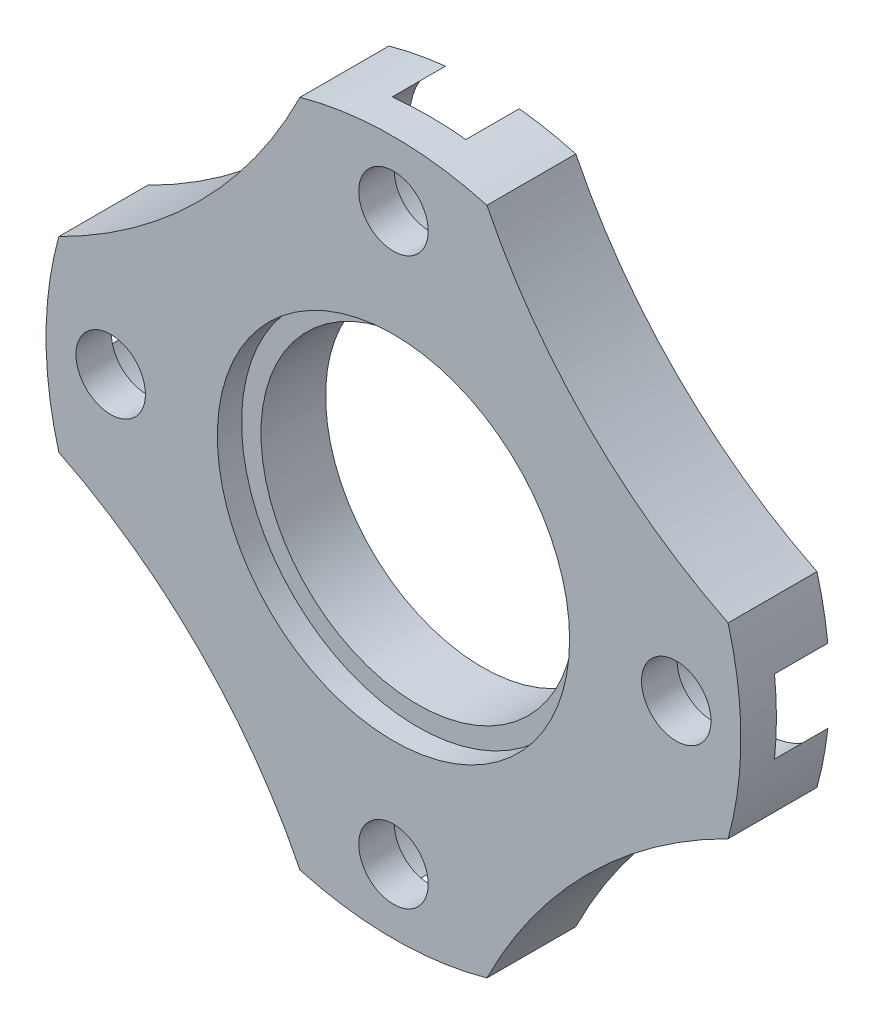
SolidWorks part; units mm, degrees
material "硅橡胶"
ref_plane "前视基准面" through (0, 0, 0) normal (0, 0, 1) x (1, 0, 0)
ref_plane "上视基准面" through (0, 0, 0) normal (0, 1, 0) x (1, 0, 0)
ref_plane "右视基准面" through (0, 0, 0) normal (1, 0, 0) x (0, 0, -1)
sketch "草图1" plane through (0, 0, 0) normal (0, 0, 1) x (1, 0, 0)
  line L0 (0, 0) -> (0, 17.5) construction
  line L1 (0, 0) -> (-17.5, 0) construction
  line L2 (0, 0) -> (17.5, 0) construction
  line L3 (0, 0) -> (0, -17.5) construction
  circle A0 centre (0, 0) radius 21.5
  circle A1 centre (0, 17.5) radius 2.15
  circle A2 centre (17.5, 0) radius 2.15
  circle A3 centre (-17.5, 0) radius 2.15
  circle A4 centre (0, -17.5) radius 2.15
  circle A5 centre (0, 0) radius 9.7
  dimension "D1" = 43
  dimension "D6" = 4.3
  dimension "D7" = 4.3
  dimension "D8" = 4.3
  dimension "D9" = 4.3
  dimension "D10" = 19.4
  dimension "D2" = 17.5
  dimension "D3" = 17.5
  dimension "D4" = 17.5
  dimension "D5" = 17.5
extrude "凸台-拉伸1" add sketch "草图1" along normal blind 5.5
sketch "草图2" plane through (0, 0, 5.5) normal (0, 0, 1) x (1, 0, 0)
  circle A0 centre (0, 0) radius 9.55
  circle A1 centre (0, 0) radius 10.9
  dimension "D1" = 19.1
  dimension "D2" = 21.8
extrude "切除-拉伸1" cut sketch "草图2" against normal blind 1.5
sketch "草图3" plane through (0, 0, 5.5) normal (0, 0, 1) x (1, 0, 0)
  line L0 (0, 0) -> (-35.3553, 35.3553) construction
  line L1 (0, 0) -> (35.3553, 35.3553) construction
  line L2 (0, 0) -> (-35.3553, -35.3553) construction
  line L3 (0, 0) -> (35.3553, -35.3553) construction
  line L4 (0, 0) -> (0, 17.5) construction
  arc A0 (5.7845, 20.7072) -> (20.7072, 5.7845) centre (35.3553, 35.3553) ccw
  arc A1 (-20.7072, 5.7845) -> (-5.7845, 20.7072) centre (-35.3553, 35.3553) ccw
  arc A2 (-5.7845, -20.7072) -> (-20.7072, -5.7845) centre (-35.3553, -35.3553) ccw
  arc A3 (20.7072, -5.7845) -> (5.7845, -20.7072) centre (35.3553, -35.3553) ccw
  arc A4 (-20.7072, -5.7845) -> (-5.7845, -20.7072) centre (0, 0) ccw
  arc A5 (-5.7845, 20.7072) -> (-20.7072, 5.7845) centre (0, 0) ccw
  arc A6 (20.7072, 5.7845) -> (5.7845, 20.7072) centre (0, 0) ccw
  arc A7 (5.7845, -20.7072) -> (20.7072, -5.7845) centre (0, 0) ccw
  dimension "D9" = 66
  dimension "D10" = 66
  dimension "D11" = 66
  dimension "D12" = 66
  dimension "D13" = 43
  dimension "D1" = 45
  dimension "D2" = 90
  dimension "D3" = 90
  dimension "D4" = 90
  dimension "D5" = 50
  dimension "D6" = 50
  dimension "D7" = 50
  dimension "D8" = 50
extrude "切除-拉伸2" cut sketch "草图3" against normal through all
sketch "草图4" plane through (0, 0, 0) normal (0, 0, -1) x (-1, 0, 0)
  circle A0 centre (0, 17.5) radius 4.5
  circle A1 centre (17.5, 0) radius 4.5
  circle A2 centre (-17.5, 0) radius 4.5
  circle A3 centre (0, -17.5) radius 4.5
  dimension "D1" = 9
  dimension "D2" = 9
  dimension "D3" = 9
  dimension "D4" = 9
extrude "切除-拉伸3" cut sketch "草图4" against normal blind 3.3
